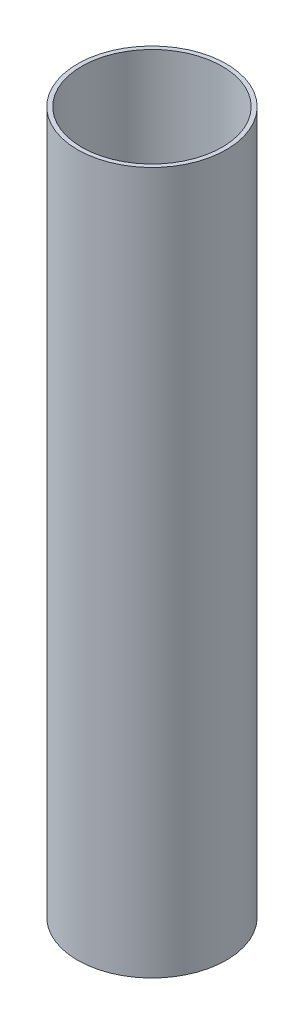
SolidWorks part; units mm, degrees
ref_plane "Front Plane" through (0, 0, 0) normal (0, 0, 1) x (1, 0, 0)
ref_plane "Top Plane" through (0, 0, 0) normal (0, 1, 0) x (1, 0, 0)
ref_plane "Right Plane" through (0, 0, 0) normal (1, 0, 0) x (0, 0, -1)
sketch "Sketch1" plane through (0, 0, 0) normal (0, 1, 0) x (1, 0, 0)
  circle A0 centre (0, 0) radius 50
  circle A1 centre (0, 0) radius 53
  dimension "D1" = 100
  dimension "D2" = 3
extrude "Boss-Extrude1" add sketch "Sketch1" along normal blind 500
